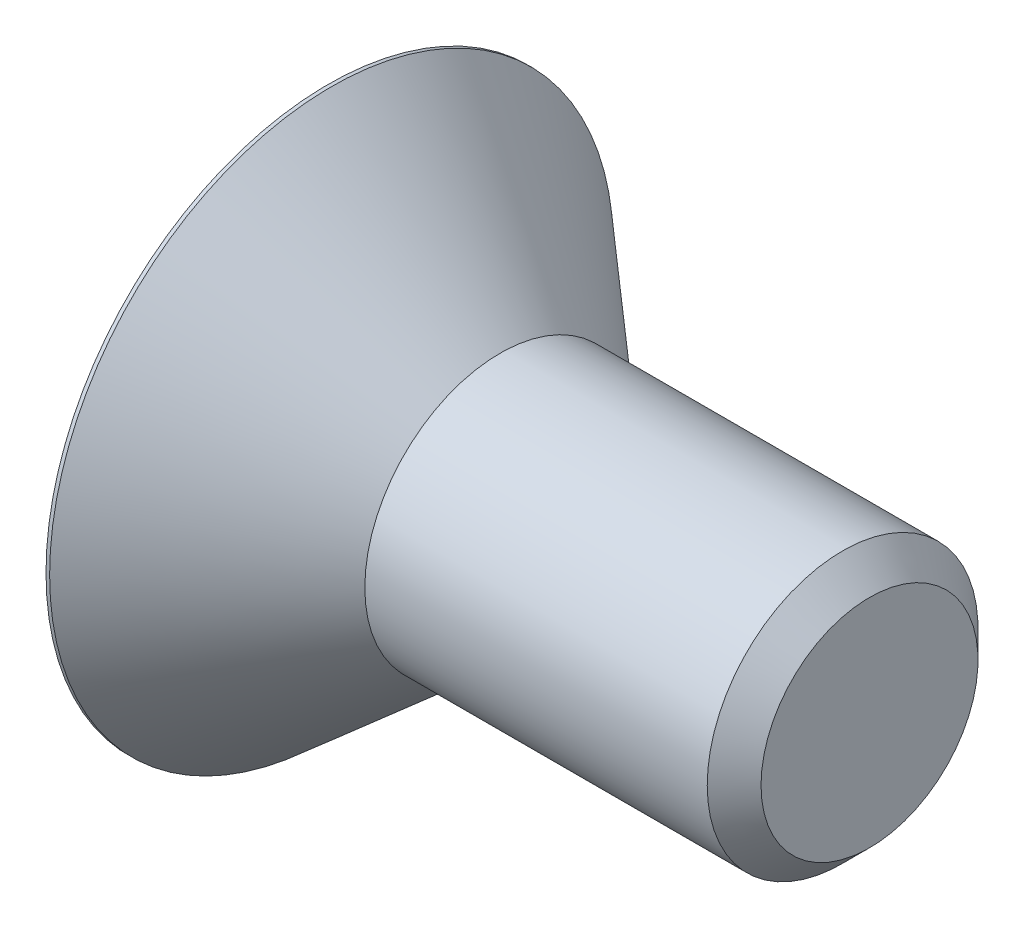
SolidWorks part; units mm, degrees
ref_plane "Plane1"
ref_plane "Plane2" through (0, 0, 0) normal (0, 1, 0) x (1, 0, 0)
ref_plane "Plane3" through (0, 0, 0) normal (1, 0, 0) x (0, 0, -1)
sketch "BodySke" plane through (0, 0, 0) normal (0, 0, 1) x (1, 0, 0)
  line L0 (0, 0) -> (0, 9.9187)
  line L1 (0.127, 9.9187) -> (6.0585, 4.7625)
  line L2 (0, 9.9187) -> (0.127, 9.9187)
  line L3 (6.0585, 4.7625) -> (18.1039, 4.7625)
  line L4 (19.05, 3.8163) -> (19.05, 0)
  line L5 (19.05, 0) -> (0, 0)
  line L6 (0, 0) -> (127, 0) construction
  line L7 (0.127, -9.9187) -> (6.0585, -4.7625) construction
  line L8 (19.05, 3.8163) -> (18.1039, 4.7625)
  line L9 (0, -9.9187) -> (0.127, -9.9187) construction
  line L10 (19.05, -3.8163) -> (18.1039, -4.7625) construction
  line L11 (7.646, 11.1125) -> (7.646, -11.1125) construction
  line L12 (0, 19.05) -> (0, -3.175) construction
  dimension "D1" = 0.127
  dimension "Diameter" = 9.525
  dimension "Length" = 19.05
  dimension "Body_ch_ang" = 45
  dimension "Head_dia" = 19.8374
  dimension "Minor_dia" = 7.6327
  dimension "Head_ang" = 82
  dimension "Advance" = 1.5875
  dimension "Thread_nom" = 19.05
revolve "BaseBody" add sketch "BodySke" angle 360 about L6
cosmetic thread "ThreadCosmetic" parameters "Thread_length"=11.531, "Thread_minor"=7.6327
sketch "Sketch2" plane through (0, 0, 0) normal (0, 0, 1) x (1, 0, 0)
  line L0 (0, 2.7788) -> (4.0386, 2.7788)
  line L1 (4.0386, 2.7788) -> (5.6429, 0)
  line L2 (0, 0) -> (127, 0) construction
  line L3 (5.6429, 0) -> (0, 0)
  line L4 (0, 0) -> (0, 2.7788)
  line L5 (0, -2.7788) -> (4.0386, -2.7788) construction
  line L6 (0, 0) -> (47.625, 0) construction
  line L8 (0, 9.9187) -> (0, -9.9187) construction
  dimension "D2" = 60
  dimension "PreBroach_depth" = 4.0386
  dimension "PreBroach_dia" = 5.5575
revolve "PreBroach" cut sketch "Sketch2" angle 360 about L6
sketch "Sketch3" plane through (0, 0, 0) normal (-1, 0, 0) x (0, 0, 1)
  line L0 (-2.7788, -1.6043) -> (-2.7788, 1.6043)
  line L1 (-2.7788, 1.6043) -> (0, 3.2086)
  line L2 (0, 3.2086) -> (2.7788, 1.6043)
  line L3 (2.7788, 1.6043) -> (2.7788, -1.6043)
  line L4 (2.7788, -1.6043) -> (0, -3.2086)
  line L5 (0, -3.2086) -> (-2.7788, -1.6043)
  dimension "D1" = 2.7788
  dimension "D2" = 2.7788
  dimension "D3" = 5.5575
  dimension "Hex_size" = 5.5575
extrude "Hex" cut sketch "Sketch3" against normal blind 4.0386
sketch "Sketch4" plane through (0, 0, 0) normal (-1, 0, 0) x (0, 0, 1)
  line L0 (0, 0) -> (3.2512, 0)
  line L1 (0, 0) -> (6.1484, 3.5498) construction
  line L2 (0, 0) -> (1.6256, 2.8156)
  line L3 (2.7204, 0.6907) -> (3.1182, 0.9204)
  line L4 (1.9584, 2.0106) -> (2.3562, 2.2402)
  arc A0 (2.7204, 0.6907) -> (1.9584, 2.0106) centre (0, 0) ccw
  arc A1 (3.2512, 0) -> (3.1182, 0.9204) centre (0, 0) ccw
  arc A2 (1.6256, 2.8156) -> (2.3562, 2.2402) centre (0, 0) cw
  dimension "D1" = 30
  dimension "Spline_n_dim" = 5.6134
  dimension "Spline_m_dim" = 6.5024
  dimension "D2" = 60
  dimension "D3" = 0.762
  dimension "Spline_p_dim" = 1.524
extrude "Spline" [suppressed] cut sketch "Sketch4" against normal blind 4.0386
pattern_circular "CirPattern1" [suppressed] count 6 every 60 about axis through (0, 0, 0) along (1, 0, 0)
sketch "ThdSchSke" plane through (0, 0, 0) normal (0, 0, 1) x (1, 0, 0)
  line L0 (7.5191, -3.8163) -> (6.8566, -4.7625)
  line L1 (7.5191, -3.8163) -> (8.1816, -4.7625)
  line L2 (8.1816, -4.7625) -> (8.1816, -5.9531)
  line L3 (-3.175, 0) -> (5.1513, 0) construction
  line L4 (0, 9.9187) -> (0, -9.9187) construction
  line L5 (8.1816, -5.9531) -> (6.8566, -5.9531)
  line L6 (6.8566, -5.9531) -> (6.8566, -4.7625)
  dimension "Thread_minor" = 7.6327
  dimension "Diameter" = 9.525
  dimension "Start" = 7.5191
  dimension "SideAngle" = 55
  dimension "VeeAngle" = 70
  dimension "Overcut" = 11.9063
revolve "ThreadSchematic" [suppressed] cut sketch "ThdSchSke" angle 360 about L3
pattern_linear "ThdSchPat" [suppressed]
equation "\"D3@Sketch4\" = \"Spline_p_dim@Sketch4\" / 2"
equation "\"Thread_minor@ThreadCosmetic\"  =  \"Minor_dia@BodySke\""
equation "\"D2@CirPattern1\" = 360 / \"Num_teeth@CirPattern1\""
equation "\"D1@Sketch3\" = \"Hex_size@Sketch3\" / 2"
equation "\"D2@Sketch3\" = \"D1@Sketch3\""
equation "\"D3@Sketch3\" = \"Hex_size@Sketch3\""
equation "\"Thread_length@ThreadCosmetic\" = ((sgn( (\"Length@BodySke\" - \"Advance@BodySke\" - ( ( ( \"Head_dia@BodySke\" - \"Diameter@BodySke\" ) * 0.5 ) / tan( \"Head_ang@BodySke\" * 0.008726646 ) ) ) - \"Thread_nom@BodySke\" )-1)*( (\"Length@BodySke\" - \"Advance@BodySke\" - ( ( ( \"Head_dia@BodySke\" - \"Diameter@BodySke\" ) * 0.5 ) / tan( \"Head_ang@BodySke\" * 0.008726646 ) ) ) - \"Thread_nom@BodySke\" ))/-2+ \"Thread_nom@BodySke\""
equation "\"Thread_minor@ThdSchSke\" = \"Minor_dia@BodySke\""
equation "\"Diameter@ThdSchSke\" = \"Diameter@BodySke\""
equation "\"Overcut@ThdSchSke\" = \"Diameter@BodySke\" * 1.25"
equation "\"Start@ThdSchSke\" = 0.000001 + \"Length@BodySke\" - \"Thread_length@ThreadCosmetic\"  '---Countersunk---"
equation "\"Num_threads@ThdSchPat\" = int( \"Thread_length@ThreadCosmetic\" / \"Advance@BodySke\" + 0.999 )  + 1"
equation "\"Advance@ThdSchPat\" = \"Thread_length@ThreadCosmetic\" /  (\"Num_threads@ThdSchPat\" - 1) 'relax it"
equation "\"Num_threads@ThdSchPat\" = \"Num_threads@ThdSchPat\" - sgn( \"Num_threads@ThdSchPat\" - 1) '---chamfered tips only---"
